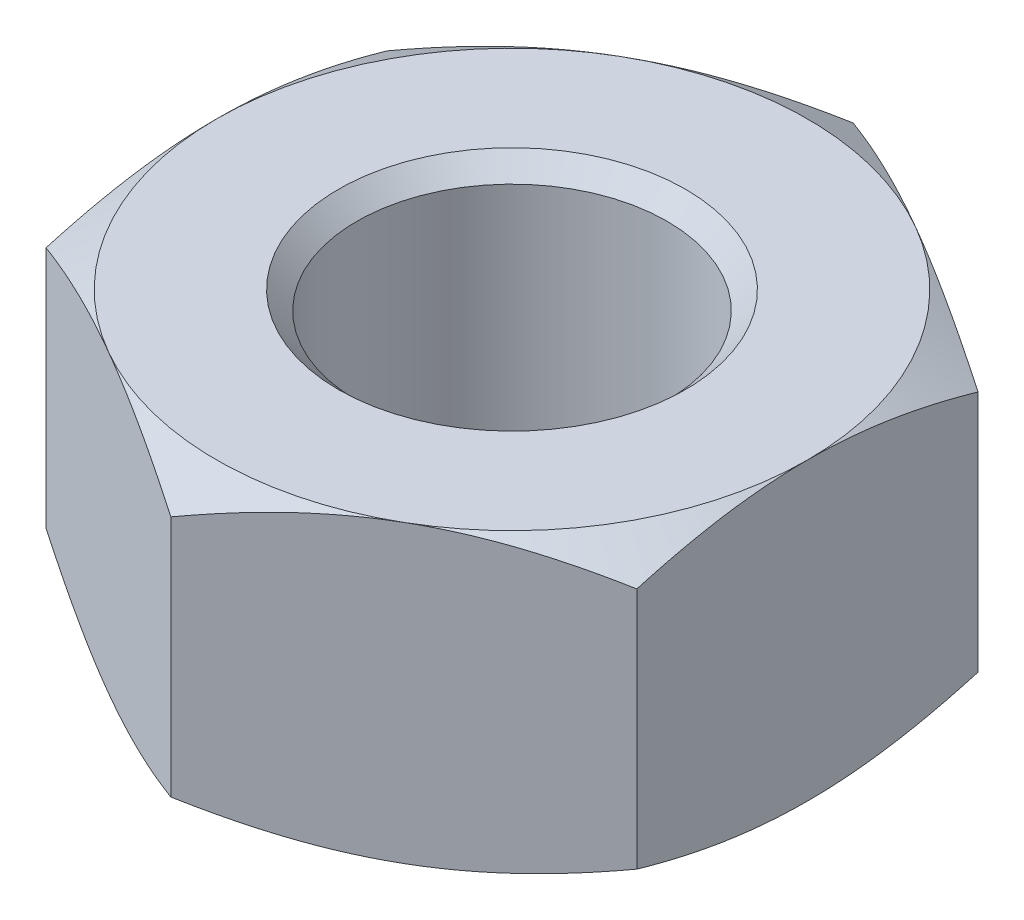
SolidWorks part; units mm, degrees
ref_plane "Front Plane" through (0, 0, 0) normal (0, 0, 1) x (1, 0, 0)
ref_plane "Top Plane" through (0, 0, 0) normal (0, 1, 0) x (1, 0, 0)
ref_plane "Right Plane" through (0, 0, 0) normal (1, 0, 0) x (0, 0, -1)
sketch "Sketch1" plane through (0, 0, 0) normal (0, 1, 0) x (1, 0, 0)
  line L1 (4, -2.3094) -> (4, 2.3094)
  line L2 (4, 2.3094) -> (0, 4.6188)
  line L3 (0, 4.6188) -> (-4, 2.3094)
  line L4 (-4, 2.3094) -> (-4, -2.3094)
  line L5 (-4, -2.3094) -> (0, -4.6188)
  line L6 (0, -4.6188) -> (4, -2.3094)
  circle A0 centre (0, 0) radius 4 construction
  dimension "D1" = 8
extrude "Boss-Extrude1" add sketch "Sketch1" along normal mid plane 4
sketch "Sketch2" plane through (0, 2, 0) normal (0, 1, 0) x (1, 0, 0)
  line L0 (4, 2.3094) -> (0, 4.6188) construction
  circle A0 centre (0, 0) radius 4
extrude "Cut-Extrude1" cut sketch "Sketch2" against normal blind 2.4 draft 60 flip side to cut
mirror "Mirror1" about plane through (0, 0, 0) normal (0, 1, 0) of "Cut-Extrude1"
hole_wizard " Tapped Hole0" positions "Sketch3" profile "Sketch4" tap size "M5" standard "ISO" end condition up to next
sketch "Sketch3" plane through (0, -2, 0) normal (0, -1, 0) x (-1, 0, 0)
  point P0 (0, 0)
sketch "Sketch4" plane through (0, -2, 0) normal (1, 0, 0) x (0, 0, -1)
  line L0 (0, 0) -> (0, 4)
  line L1 (0, 4) -> (2.1, 4)
  line L2 (2.1, 4) -> (2.1, 0)
  line L5 (2.1, 0) -> (0, 0)
  line L11 (0, -6.35) -> (0, 107.95) construction
  dimension "Thru Tap Drill Dia." = 4.2
  dimension "Thru Tap Drill Depth" = 4
cosmetic thread "Hole Thread1" parameters "D2"=5
chamfer "Chamfer1" distance 0.25 angle 45 2 edges at (0, 2, 2.1) (0, -2, -2.1)
